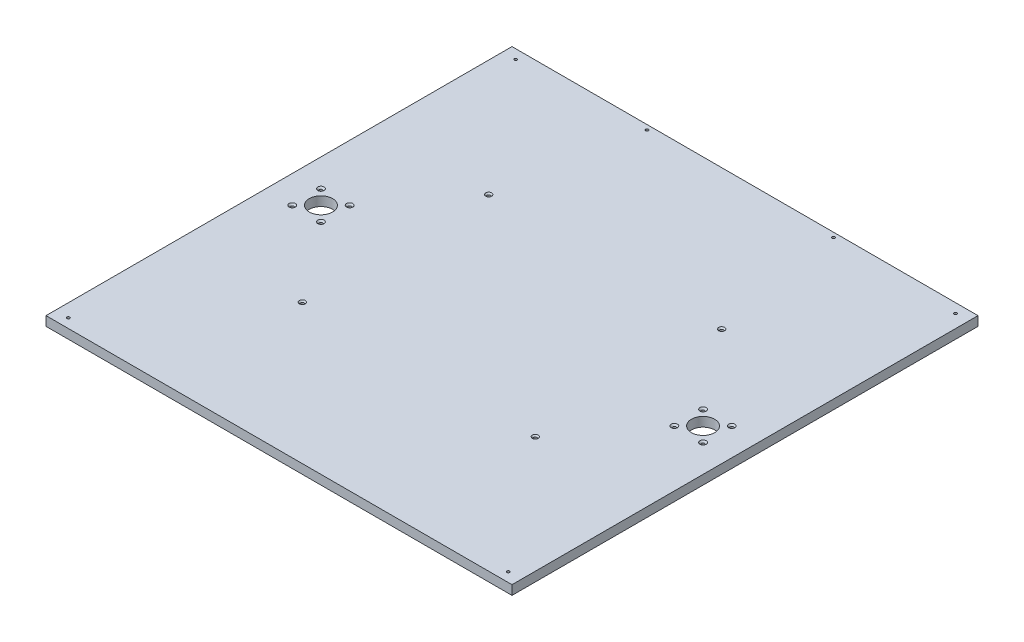
SolidWorks part; units mm, degrees
ref_plane "Płaszczyzna przednia" through (0, 0, 0) normal (0, 0, 1) x (1, 0, 0)
ref_plane "Płaszczyzna górna" through (0, 0, 0) normal (0, 1, 0) x (1, 0, 0)
ref_plane "Płaszczyzna prawa" through (0, 0, 0) normal (1, 0, 0) x (0, 0, -1)
sketch "Szkic1" plane through (0, 0, 0) normal (0, 1, 0) x (1, 0, 0)
  line L1 (0, 0) -> (500, 0)
  line L2 (0, 0) -> (0, 500)
  line L3 (0, 500) -> (500, 500)
  line L4 (500, 0) -> (500, 500)
  dimension "D1" = 500
  dimension "D2" = 500
extrude "Dodanie-wyciągnięcie1" add sketch "Szkic1" along normal blind 10
sketch "Szkic2" plane through (0, 10, 0) normal (0, 1, 0) x (1, 0, 0)
  line L0 (0, 500) -> (0, 0) construction
  line L1 (500, 500) -> (0, 500) construction
  line L3 (500, 0) -> (500, 500) construction
  circle A0 centre (45, 250) radius 12.5
  circle A1 centre (455, 250) radius 12.5
  dimension "D1" = 25
  dimension "D2" = 45
  dimension "D3" = 250
  dimension "D4" = 25
  dimension "D5" = 45
extrude "Wytnij-wyciągnięcie1" cut sketch "Szkic2" against normal through all
sketch "Szkic5" plane through (0, 10, 0) normal (0, 1, 0) x (1, 0, 0)
  line L0 (0, 500) -> (0, 0) construction
  line L1 (0, 0) -> (500, 0) construction
  circle A0 centre (125, 150) radius 1.6
  circle A1 centre (375, 150) radius 1.6
  circle A2 centre (375, 350) radius 1.6
  circle A3 centre (125, 350) radius 1.6
  dimension "D1" = 3.2
  dimension "D2" = 125
  dimension "D3" = 150
  dimension "D4" = 2
  dimension "D5" = 2
hole_wizard "Pogłębienie stożkowe pod M3 Wkręt ustalający1" positions "Szkic6" profile "Szkic7" countersink size "M3" standard "Ansi Metric" end condition through all
sketch "Szkic6" plane through (0, 10, 0) normal (0, 1, 0) x (1, 0, 0)
  point P0 (439.6, 265.4)
  point P3 (439.6, 234.6)
  point P6 (470.4, 234.6)
  point P9 (470.4, 265.4)
  point P12 (60.4, 234.6)
  point P15 (60.4, 265.4)
  point P18 (29.6, 234.6)
  point P21 (29.6, 265.4)
sketch "Szkic7" plane through (439.6, 10, -265.4) normal (1, 0, 0) x (0, 0, 1)
  line L0 (0, 0) -> (0, 10)
  line L1 (0, 10) -> (1.7, 10)
  line L2 (1.7, 10) -> (1.7, 1.66)
  line L3 (1.7, 1.66) -> (3.36, 0)
  line L5 (3.36, 0) -> (0, 0)
  line L6 (-1.7, 1.66) -> (-3.36, 0) construction
  line L11 (0, -6.35) -> (0, 107.95) construction
  dimension "Œrednica otworu na wylot" = 3.4
  dimension "G³êbokoœæ otworu na wylot" = 10
  dimension "Œrednica zewnêtrznego pog³êbienia sto¿kowego" = 6.72
  dimension "K¹t zewnêtrznego pog³êbienia sto¿kowego" = 90
hole_wizard "Pogłębienie stożkowe pod M3 wkręt do części metalowych z łbem soczewkowym1" positions "Szkic8" profile "Szkic9" countersink size "M3" standard "Ansi Metric"
sketch "Szkic8" plane through (0, 10, 0) normal (0, 1, 0) x (1, 0, 0)
  point P0 (375, 350)
  point P3 (375, 150)
  point P6 (125, 350)
  point P9 (125, 150)
sketch "Szkic9" plane through (375, 10, -350) normal (1, 0, 0) x (0, 0, 1)
  line L0 (0, 0) -> (0, 11.0215)
  line L1 (0, 11.0215) -> (1.7, 10)
  line L2 (1.7, 10) -> (1.7, 1.45)
  line L3 (1.7, 1.45) -> (3.15, 0)
  line L5 (3.15, 0) -> (0, 0)
  line L6 (-1.7, 1.45) -> (-3.15, 0) construction
  line L10 (0, 11.0215) -> (-1.7, 10) construction
  line L11 (0, -6.35) -> (0, 107.95) construction
  dimension "Œrednica otworu" = 3.4
  dimension "G³êbokoœc otworu" = 10
  dimension "Œrednica zewnêtrznego pog³êbienia sto¿kowego" = 6.3
  dimension "K¹t zewnêtrznego pog³êbienia sto¿kowego" = 90
  dimension "K¹t wiert³a" = 118
hole_wizard "Otwory ustalające Ø3.0mm1" positions "Szkic10" profile "Szkic11" hole size "Ø3.0" standard "Ansi Metric"
sketch "Szkic10" plane through (0, 0, 0) normal (0, -1, 0) x (-1, 0, 0)
  line L0 (-10, 0) -> (-10, 500) construction
  line L2 (-500, 500) -> (0, 500) construction
  line L3 (-490, 500) -> (-490, 0) construction
  line L4 (0, 0) -> (-500, 0) construction
  point P0 (-486, 490)
  point P2 (-486, 10)
  point P4 (-14, 10)
  point P6 (-14, 490)
  point P45 (0, 0)
  point P46 (0, 0)
  dimension "D1" = 4
  dimension "D2" = 10
  dimension "D3" = 4
  dimension "D4" = 10
  dimension "D5" = 4
  dimension "D6" = 10
  dimension "D7" = 4
  dimension "D8" = 10
sketch "Szkic11" plane through (486, 0, -490) normal (1, 0, 0) x (0, 0, -1)
  line L0 (0, 0) -> (0, 10.9013)
  line L1 (0, 10.9013) -> (1.5, 10)
  line L2 (1.5, 10) -> (1.5, 0)
  line L5 (1.5, 0) -> (0, 0)
  line L10 (0, 10.9013) -> (-1.5, 10) construction
  line L11 (0, -6.35) -> (0, 107.95) construction
  dimension "Œrednica otworu" = 3
  dimension "G³êbokoœæ otworu" = 10
  dimension "K¹t wiert³a" = 118
hole_wizard "Otwory ustalające Ø3.0mm2" positions "Szkic12" profile "Szkic13" hole size "Ø3.0" standard "Ansi Metric"
sketch "Szkic12" plane through (0, 0, 0) normal (0, -1, 0) x (-1, 0, 0)
  line L0 (-500, 500) -> (0, 500) construction
  line L1 (0, 500) -> (0, 0) construction
  line L2 (-500, 0) -> (-500, 500) construction
  point P0 (-150, 495)
  point P2 (-350, 495)
  dimension "D1" = 5
  dimension "D2" = 150
  dimension "D3" = 5
  dimension "D4" = 150
sketch "Szkic13" plane through (150, 0, -495) normal (1, 0, 0) x (0, 0, -1)
  line L0 (0, 0) -> (0, 10.9013)
  line L1 (0, 10.9013) -> (1.5, 10)
  line L2 (1.5, 10) -> (1.5, 0)
  line L5 (1.5, 0) -> (0, 0)
  line L10 (0, 10.9013) -> (-1.5, 10) construction
  line L11 (0, -6.35) -> (0, 107.95) construction
  dimension "Œrednica otworu" = 3
  dimension "G³êbokoœæ otworu" = 10
  dimension "K¹t wiert³a" = 118
